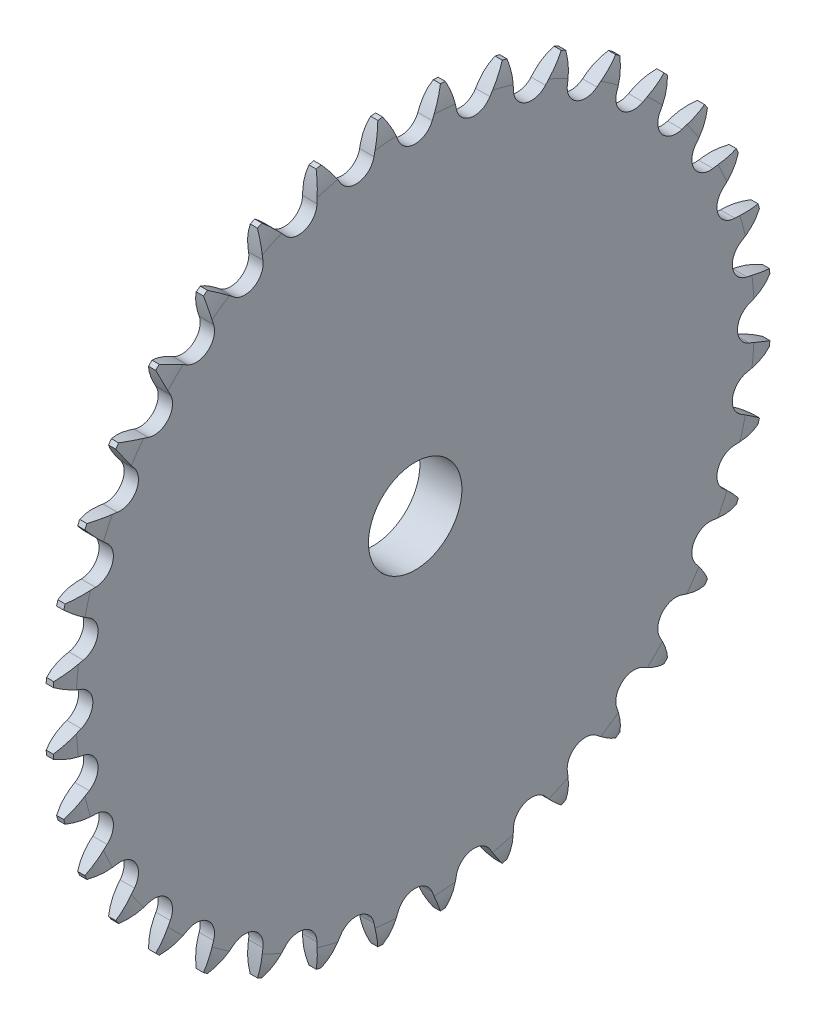
SolidWorks part; units mm, degrees
ref_plane "Plane1" through (0, 0, 0) normal (0, 0, 1) x (1, 0, 0)
ref_plane "Plane2" through (0, 0, 0) normal (0, 1, 0) x (1, 0, 0)
ref_plane "Plane3" through (0, 0, 0) normal (1, 0, 0) x (0, 0, -1)
sketch "Clipboard" plane through (0, 0, 0) normal (0, 1, 0) x (1, 0, 0)
  line L0 (0, 0) -> (10.2745, -7.4649)
  line L1 (-15, 0) -> (100, 0) construction
  line L2 (0, 0) -> (-0.5049, 0.5707)
  line L3 (0, 0) -> (-11.863, 4.5341)
  line L4 (0, 0) -> (2.508, 1.8221)
  line L5 (0, 0) -> (-8.4326, -3.1451)
  line L6 (0, 0) -> (-2.5441, -1.7165)
  line L7 (-0.5049, 0.5707) -> (6.6832, 5.9873)
  line L8 (-76.2, 38.1) -> (-73.4, 38.1)
  line L9 (-73.2427, 39.6204) -> (-72.6435, 39.6525)
  line L10 (-73.1375, 10.4807) -> (-66.1375, 10.4807)
  circle A0 centre (0, 0) radius 3.875
  circle A1 centre (0, 0) radius 31
  circle A2 centre (0, 0) radius 31
  dimension "Dr" = 7.75
  dimension "MHD" = 62
  dimension "Hub_dia" = 62
  dimension "Num_teeth" = 36
  dimension "Pitch" = 12.7
  dimension "Width" = 3.1
  dimension "Side_relief" = 0.762
  dimension "Side_radius" = 12.7
  dimension "Overall_len" = 9
  dimension "Show_teeth" = 36
  dimension "Thickness" = 3.069
  dimension "OAL" = 9.0005
  dimension "T_dim" = 2.8
  dimension "Fillet_rad" = 0.6
  dimension "Face_width" = 3.069
  dimension "Num_strands" = 1
  dimension "Transv_pitch" = 7
  dimension "Plate_wid" = 9.91
sketch "BasProSke" plane through (0, 0, 0) normal (0, 1, 0) x (1, 0, 0)
  line L0 (-10, 0) -> (60, 0) construction
  line L1 (0, 0) -> (0, 72.5877)
  line L2 (0, 0) -> (3.069, 0)
  line L3 (3.069, 0) -> (3.069, 72.5877)
  line L4 (2.307, 76.9206) -> (0.762, 76.9206)
  arc A0 (0, 72.5877) -> (0.762, 76.9206) centre (12.7, 72.5877) cw
  arc A1 (3.069, 72.5877) -> (2.307, 76.9206) centre (-9.631, 72.5877) ccw
  dimension "Thickness" = 3.069
  dimension "D1" = 12.7
  dimension "G1" = 0.762
  dimension "G2" = 0.762
  dimension "Diameter" = 153.8412
revolve "Base-Revolve" add sketch "BasProSke" angle 360 about L0
sketch "TooCutSke" plane through (0, 0, 0) normal (1, 0, 0) x (0, 0, -1)
  line L0 (0, 72.8968) -> (3.6476, 71.4783) construction
  line L1 (0, 0) -> (0, 107) construction
  line L2 (0, 72.8968) -> (-10, 72.8968) construction
  line L3 (0, 72.8968) -> (-3.6476, 71.4783) construction
  arc A0 (3.6476, 71.4783) -> (6.462, 77.1504) centre (36.5848, 58.6698) cw
  arc A1 (3.6476, 71.4783) -> (-3.6476, 71.4783) centre (0, 72.8968) cw
  arc A2 (-3.6476, 71.4783) -> (-6.462, 77.1504) centre (-36.5848, 58.6698) ccw
  arc A3 (6.462, 77.1504) -> (-6.462, 77.1504) centre (0, 0) ccw
  dimension "R1" = 3.9137
  dimension "R2" = 35.34
  dimension "Overcut" = 77.4206
  dimension "Seat_radius" = 72.8968
  dimension "X" = 137.5
extrude "ToothCut" cut sketch "TooCutSke" along normal through all
pattern_circular "TeethCuts" count 36 every 10 about axis through (-10, 0, 0) along (1, 0, 0) of "ToothCut"
sketch "HubNeaOneSke" plane through (0, 0, 0) normal (-1, 0, 0) x (0, 0, 1)
  circle A0 centre (0, 0) radius 31
  dimension "Diameter" = 62
extrude "HubNearOne" add sketch "HubNeaOneSke" along normal blind 5.9315
fillet "HubNearOneFillet" radius 0.6 1 edges at (0, 0, -31)
sketch "HubNeaBotSke" plane through (0, 0, 0) normal (-1, 0, 0) x (0, 0, 1)
  circle A0 centre (0, 0) radius 31
  dimension "Diameter" = 62
extrude "HubNearBoth" [suppressed] add sketch "HubNeaBotSke" along normal blind 2.9658
fillet "HubNearBothFillet" [suppressed] radius 0.6
ref_plane "FarPln" through (3.069, 0, 0) normal (1, 0, 0) x (0, 0, -1)
sketch "HubFarSke" plane through (3.069, 0, 0) normal (1, 0, 0) x (0, 0, -1)
  circle A0 centre (0, 0) radius 31
  dimension "Diameter" = 62
extrude "HubFar" [suppressed] add sketch "HubFarSke" along normal blind 2.9658
fillet "HubFarFillet" [suppressed] radius 0.6
sketch "BorSke" plane through (0, 0, 0) normal (1, 0, 0) x (0, 0, -1)
  circle A0 centre (0, 0) radius 10
  dimension "Diameter" = 20
extrude "Bore" cut sketch "BorSke" along normal mid plane 18.001
sketch "KeySke" plane through (0, 0, 0) normal (1, 0, 0) x (0, 0, -1)
  line L0 (-3, 0) -> (-3, 12.8)
  line L1 (-3, 12.8) -> (3, 12.8)
  line L2 (3, 12.8) -> (3, 0)
  line L3 (0, 0) -> (0, 34) construction
  line L4 (-3, 0) -> (3, 0)
  dimension "Offset" = 12.8
  dimension "Width" = 6
extrude "Keyway" [suppressed] cut sketch "KeySke" along normal mid plane 18.001
pattern_circular "Keyway2" [suppressed] count 2 every 90 about axis through (-10, 0, 0) along (1, 0, 0)
equation "' \"Pitch@Clipboard\" = 12.7"
equation "' \"Num_strands@Clipboard\" = 1"
equation "' \"Num_teeth@Clipboard\" = 9"
equation "' \"Hub_dia@Clipboard\" = 50"
equation "' \"Overall_len@Clipboard\" = 3"
equation "' \"Diameter@BorSke\" = 12"
equation "' \"T_dim@Clipboard\" = 1"
equation "' \"Width@KeySke\" = 2"
equation "' \"Dr@Clipboard\" = 8.51"
equation "' \"Face_width@Clipboard\" = 7.2"
equation "' \"Side_radius@Clipboard\" = 12.7"
equation "' \"Side_relief@Clipboard\" = 1.27"
equation "' \"Transv_pitch@Clipboard\" = 13.92"
equation "' \"Show_teeth@Clipboard\" = 9"
equation "' \"Fillet_rad@Clipboard\" = 0.6"
equation "' \"Plate_wid@Clipboard\" = 11.8"
equation "\"Num_teeth@Clipboard\" = int( \"Num_teeth@Clipboard\" )"
equation "\"Num_teeth@Clipboard\" = ((sgn( \"Num_teeth@Clipboard\" - 5.0)+1)*( \"Num_teeth@Clipboard\" - 5.0))/2 +5.0"
equation "\"Num_teeth@Clipboard\" = ((sgn( \"Num_teeth@Clipboard\" - 200.0)-1)*( \"Num_teeth@Clipboard\" - 200.0))/-2 +200.0"
equation "\"MHD@Clipboard\" = \"Pitch@Clipboard\" * (1.0 / tan(3.14159265 / \"Num_teeth@Clipboard\" )) - 1.04 * \"Plate_wid@Clipboard\" - 0.76"
equation "\"Thickness@Clipboard\"  = \"Face_width@Clipboard\" + (\"Num_strands@Clipboard\" - 1) * \"Transv_pitch@Clipboard\""
equation "\"OAL@Clipboard\" = \"Thickness@Clipboard\" + 2 * \"Fillet_rad@Clipboard\" + 1"
equation "\"MHD@Clipboard\" = ((sgn( \"MHD@Clipboard\" - \"Hub_dia@Clipboard\" )-1)*( \"MHD@Clipboard\" - \"Hub_dia@Clipboard\" ))/-2+ \"Hub_dia@Clipboard\""
equation "\"OAL@Clipboard\" = ((sgn( \"OAL@Clipboard\" - \"Overall_len@Clipboard\" )+1)*( \"OAL@Clipboard\" - \"Overall_len@Clipboard\" ))/2 + \"Overall_len@Clipboard\" + 0.0005"
equation "\"Num_teeth@TeethCuts\" = int( \"Show_teeth@Clipboard\" ) + 1"
equation "\"Num_teeth@TeethCuts\" = ((sgn( \"Num_teeth@TeethCuts\" - \"Num_teeth@Clipboard\" )-1)*( \"Num_teeth@TeethCuts\" - \"Num_teeth@Clipboard\" ))/-2+ \"Num_teeth@Clipboard\""
equation "\"Num_teeth@TeethCuts\" = ((sgn( \"Num_teeth@TeethCuts\" - 2.0)+1)*( \"Num_teeth@TeethCuts\" - 2.0))/2 +2.0"
equation "\"Angle@TeethCuts\" = 360.0 / \"Num_teeth@Clipboard\""
equation "\"Seat_radius@TooCutSke\" = ( \"Pitch@Clipboard\" / 2.0) / sin(3.14159265 / \"Num_teeth@Clipboard\" ) - \"Dr@Clipboard\" / 2.0 + \"Dr@Clipboard\" * 0.505"
equation "\"R1@TooCutSke\"  = \"Dr@Clipboard\" * 0.505"
equation "\"X@TooCutSke\" = 140.0 - (90.0 / \"Num_teeth@Clipboard\")"
equation "\"R2@TooCutSke\" = 0.12 * \"Dr@Clipboard\" * ( \"Num_teeth@Clipboard\" + 2.0)"
equation "\"Overcut@TooCutSke\" = 0.5 + 0.625 * \"Pitch@Clipboard\" - 0.5 * \"Dr@Clipboard\"  +  \"Pitch@Clipboard\" / 2.0 / sin(3.14159265 / \"Num_teeth@Clipboard\" )"
equation "\"Diameter@BasProSke\" = 2.0 * ( 0.625 * \"Pitch@Clipboard\" - 0.5 * \"Dr@Clipboard\"  +  \"Pitch@Clipboard\" / 2.0 / sin(3.14159265 / \"Num_teeth@Clipboard\" ))"
equation "\"Thickness@BasProSke\"  = \"Thickness@Clipboard\""
equation "\"G1@BasProSke\" =  \"Side_relief@Clipboard\""
equation "\"G2@BasProSke\" =  \"Side_relief@Clipboard\""
equation "\"D1@BasProSke\" =  \"Side_radius@Clipboard\""
equation "\"Diameter@HubNeaOneSke\" = \"MHD@Clipboard\""
equation "\"Length@HubNearOne\" = \"OAL@Clipboard\" - \"Thickness@BasProSke\""
equation "\"Diameter@HubNeaBotSke\" = \"MHD@Clipboard\""
equation "\"Length@HubNearBoth\" = ( \"OAL@Clipboard\" - \"Thickness@BasProSke\" ) / 2.0"
equation "\"D1@HubNearOneFillet\" = \"Fillet_rad@Clipboard\""
equation "\"D1@HubNearBothFillet\" = \"Fillet_rad@Clipboard\""
equation "\"Thickness@FarPln\" = \"Thickness@BasProSke\""
equation "\"Diameter@HubFarSke\" = \"MHD@Clipboard\""
equation "\"Length@HubFar\" = ( \"OAL@Clipboard\" - \"Thickness@BasProSke\" ) / 2.0"
equation "\"D1@HubFarFillet\" = \"Fillet_rad@Clipboard\""
equation "\"D1@Bore\" = \"OAL@Clipboard\" * 2.0"
equation "\"D1@Keyway\" = \"OAL@Clipboard\" * 2.0"
equation "\"Offset@KeySke\" = \"T_dim@Clipboard\" + \"Diameter@BorSke\" / 2.0"
